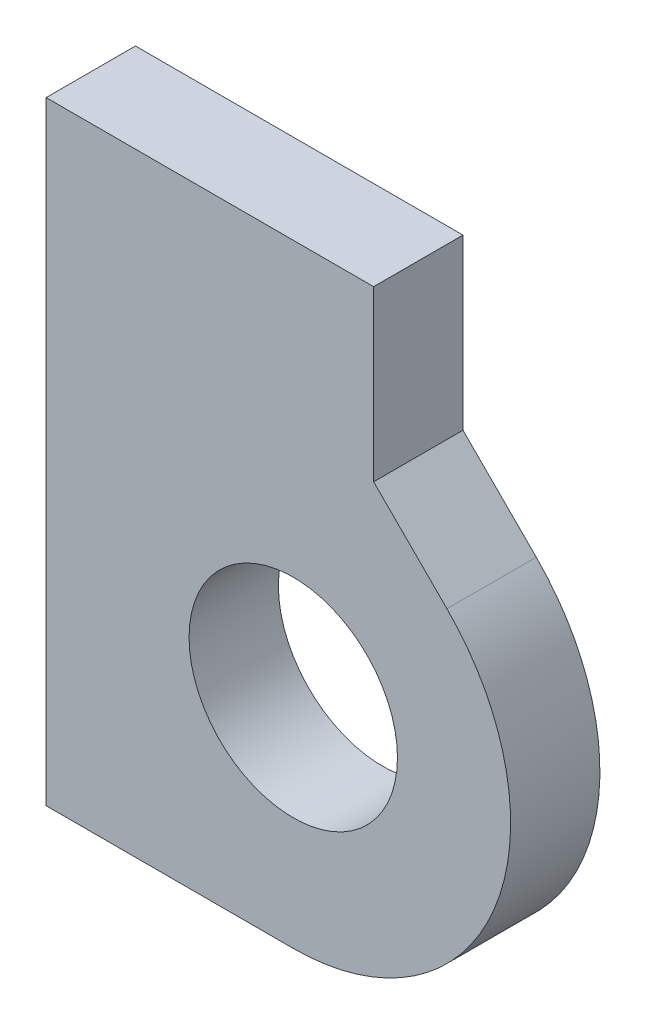
SolidWorks part; units mm, degrees
ref_plane "前视基准面" through (0, 0, 0) normal (0, 0, 1) x (1, 0, 0)
ref_plane "上视基准面" through (0, 0, 0) normal (0, 1, 0) x (1, 0, 0)
ref_plane "右视基准面" through (0, 0, 0) normal (1, 0, 0) x (0, 0, -1)
sketch "草图1" plane through (0, 0, 0) normal (0, 0, 1) x (1, 0, 0)
  line L0 (0, 0) -> (110, 0)
  line L1 (110, 0) -> (110, -56.7624)
  line L2 (0, 0) -> (0, -206)
  line L3 (0, -206) -> (83, -206)
  line L4 (110, -56.7624) -> (134.6188, -81.3812)
  circle A0 centre (83, -133) radius 35
  arc A1 (83, -206) -> (134.6188, -81.3812) centre (83, -133) ccw
  point P9 (110, -45.7968)
  dimension "D1" = 206
  dimension "D2" = 73
  dimension "D3" = 83
  dimension "D4" = 146
  dimension "D7" = 70
  dimension "D5" = 110
  dimension "D6" = 45
extrude "凸台-拉伸1" add sketch "草图1" along normal blind 30
